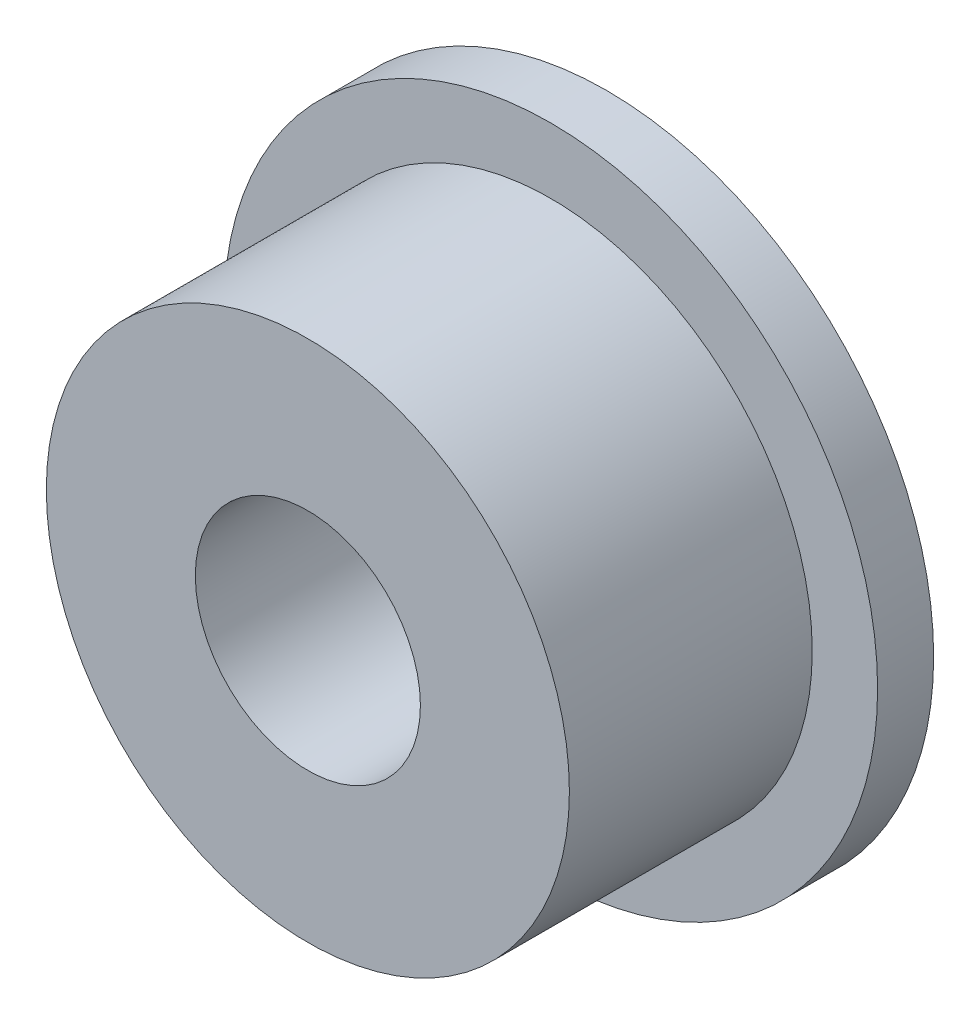
SolidWorks part; units mm, degrees
ref_plane "前视基准面" through (0, 0, 0) normal (0, 0, 1) x (1, 0, 0)
ref_plane "上视基准面" through (0, 0, 0) normal (0, 1, 0) x (1, 0, 0)
ref_plane "右视基准面" through (0, 0, 0) normal (1, 0, 0) x (0, 0, -1)
other "Configuration Table"
sketch "草图1" plane through (0, 0, 0) normal (0, 0, 1) x (1, 0, 0)
  circle A0 centre (0, 0) radius 14
  circle A1 centre (0, 0) radius 6.025
extrude "凸台-拉伸1" add sketch "草图1" along normal blind 16
sketch "草图2" plane through (0, 0, 0) normal (0, 0, 1) x (1, 0, 0)
  circle A0 centre (0, 0) radius 17.5
  circle A1 centre (0, 0) radius 6.025
extrude "凸台-拉伸2" add sketch "草图2" along normal blind 3
